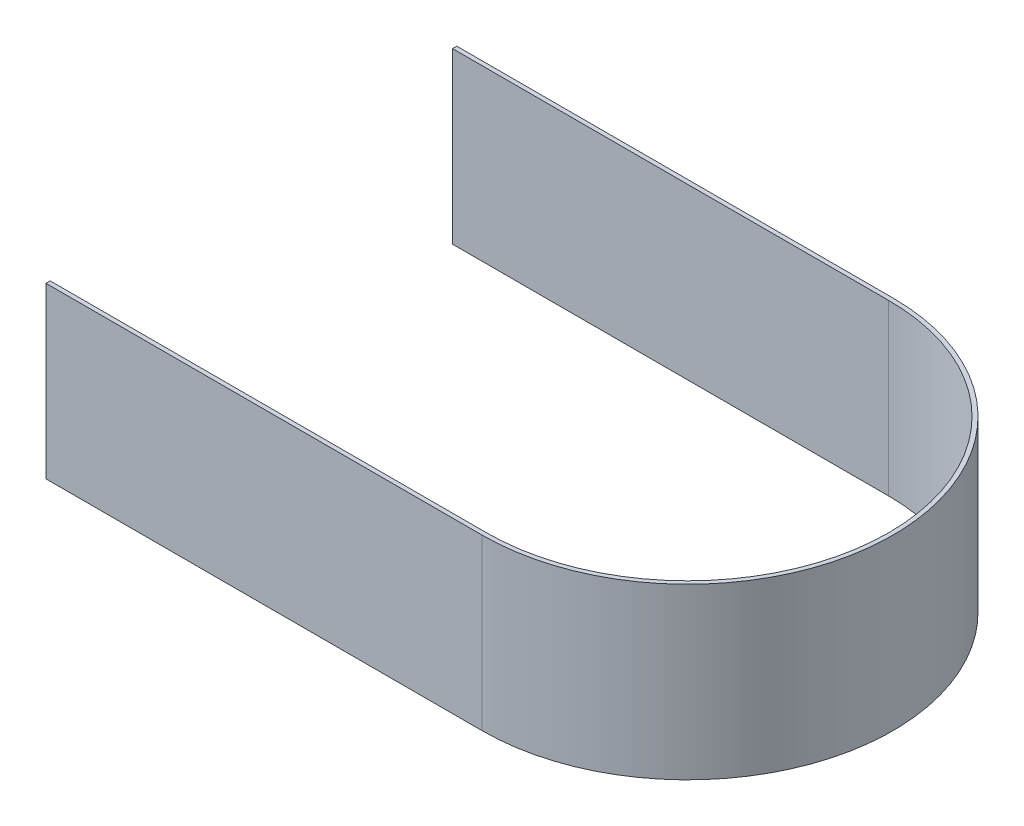
SolidWorks part; units mm, degrees
ref_plane "前视" through (0, 0, 0) normal (0, 0, 1) x (1, 0, 0)
ref_plane "上视" through (0, 0, 0) normal (0, 1, 0) x (1, 0, 0)
ref_plane "右视" through (0, 0, 0) normal (1, 0, 0) x (0, 0, -1)
sketch "Sketch1" plane through (0, 0, 0) normal (0, 1, 0) x (1, 0, 0)
  line L0 (0, 0) -> (10.3, 0)
  line L1 (10.3, 9.5) -> (0, 9.5)
  line L2 (0, 0) -> (0, -0.1)
  line L3 (0, -0.1) -> (10.3, -0.1)
  line L4 (10.3, 9.6) -> (0, 9.6)
  line L5 (0, 9.6) -> (0, 9.5)
  arc A0 (10.3, 0) -> (10.3, 9.5) centre (10.3, 4.75) ccw
  arc A1 (10.3, -0.1) -> (10.3, 9.6) centre (10.3, 4.75) ccw
  dimension "D2" = 4.75
  dimension "D4" = 4.85
  dimension "D1" = 10.3
  dimension "D3" = 0.1
extrude "Boss-Extrude1" add sketch "Sketch1" along normal blind 4
